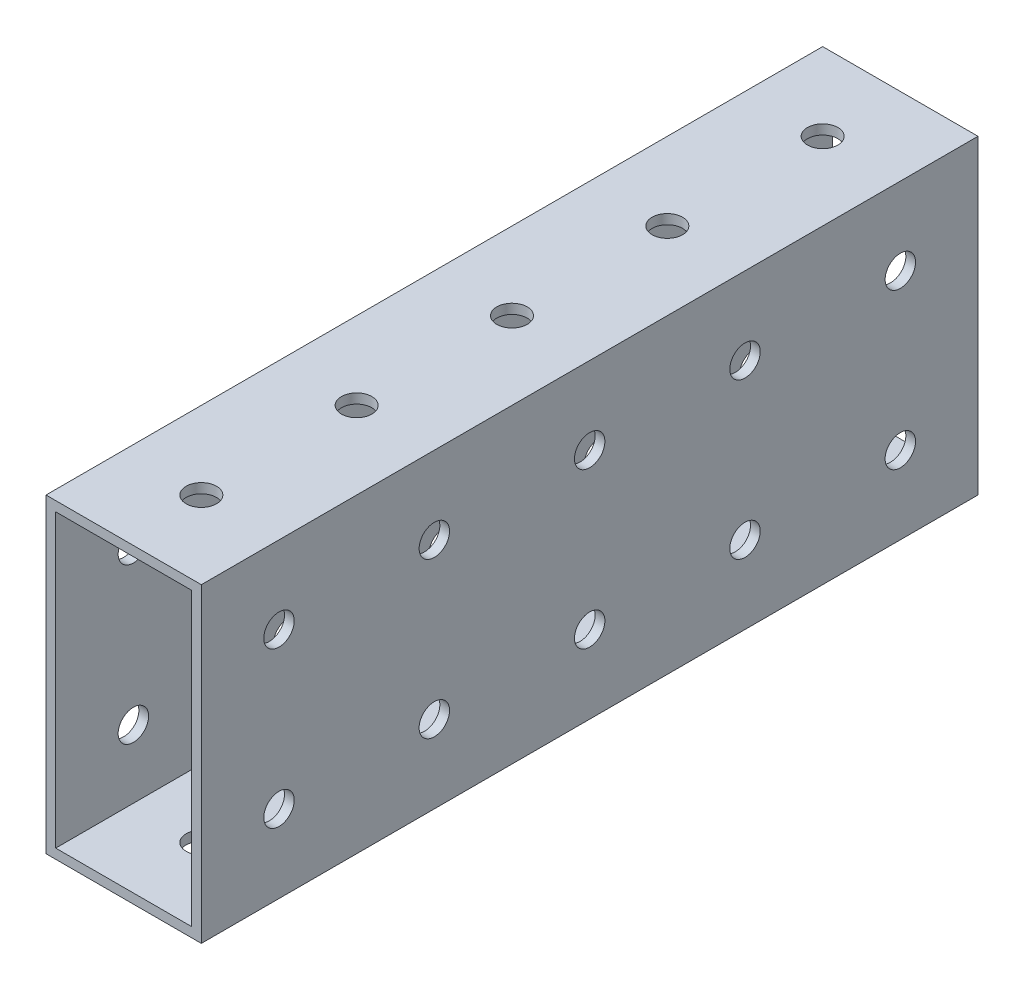
SolidWorks part; units mm, degrees
ref_plane "Front Plane" through (0, 0, 0) normal (0, 0, 1) x (1, 0, 0)
ref_plane "Top Plane" through (0, 0, 0) normal (0, 1, 0) x (1, 0, 0)
ref_plane "Right Plane" through (0, 0, 0) normal (1, 0, 0) x (0, 0, -1)
sketch "Sketch1" plane through (0, 0, 0) normal (0, 0, 1) x (1, 0, 0)
  line L1 (0, 0) -> (25.4, 0)
  line L2 (0, 0) -> (0, 50.8)
  line L3 (0, 50.8) -> (25.4, 50.8)
  line L4 (25.4, 0) -> (25.4, 50.8)
  dimension "D1" = 25.4
  dimension "D2" = 50.8
extrude "Boss-Extrude1" add sketch "Sketch1" along normal blind 127
shell "Shell1" thickness 1.5875
sketch "Sketch2" plane through (0, 0, 0) normal (-1, 0, 0) x (0, 0, 1)
  line L0 (0, 50.8) -> (0, 0) construction
  line L1 (127, 0) -> (0, 0) construction
  circle A0 centre (12.7, 12.7) radius 2.4892
  circle A1 centre (38.1, 12.7) radius 2.4892
  circle A2 centre (63.5, 12.7) radius 2.4892
  circle A3 centre (88.9, 12.7) radius 2.4892
  circle A4 centre (114.3, 12.7) radius 2.4892
  circle A5 centre (38.1, 38.1) radius 2.4892
  circle A6 centre (63.5, 38.1) radius 2.4892
  circle A7 centre (88.9, 38.1) radius 2.4892
  circle A8 centre (114.3, 38.1) radius 2.4892
  circle A9 centre (12.7, 38.1) radius 2.4892
  dimension "D3" = 4.9784
  dimension "D1" = 12.7
  dimension "D2" = 12.7
  dimension "D4" = 5
  dimension "D5" = 2
extrude "Cut-Extrude1" cut sketch "Sketch2" against normal through all
sketch "Sketch3" plane through (0, 50.8, 0) normal (0, 1, 0) x (1, 0, 0)
  line L0 (25.4, 0) -> (0, 0) construction
  line L1 (0, -127) -> (0, 0) construction
  circle A0 centre (12.7, -12.7) radius 2.4892
  circle A1 centre (12.7, -38.1) radius 2.4892
  circle A2 centre (12.7, -63.5) radius 2.4892
  circle A3 centre (12.7, -88.9) radius 2.4892
  circle A4 centre (12.7, -114.3) radius 2.4892
  dimension "D1" = 4.9784
  dimension "D2" = 12.7
  dimension "D3" = 12.7
  dimension "D4" = 5
extrude "Cut-Extrude2" cut sketch "Sketch3" against normal through all
